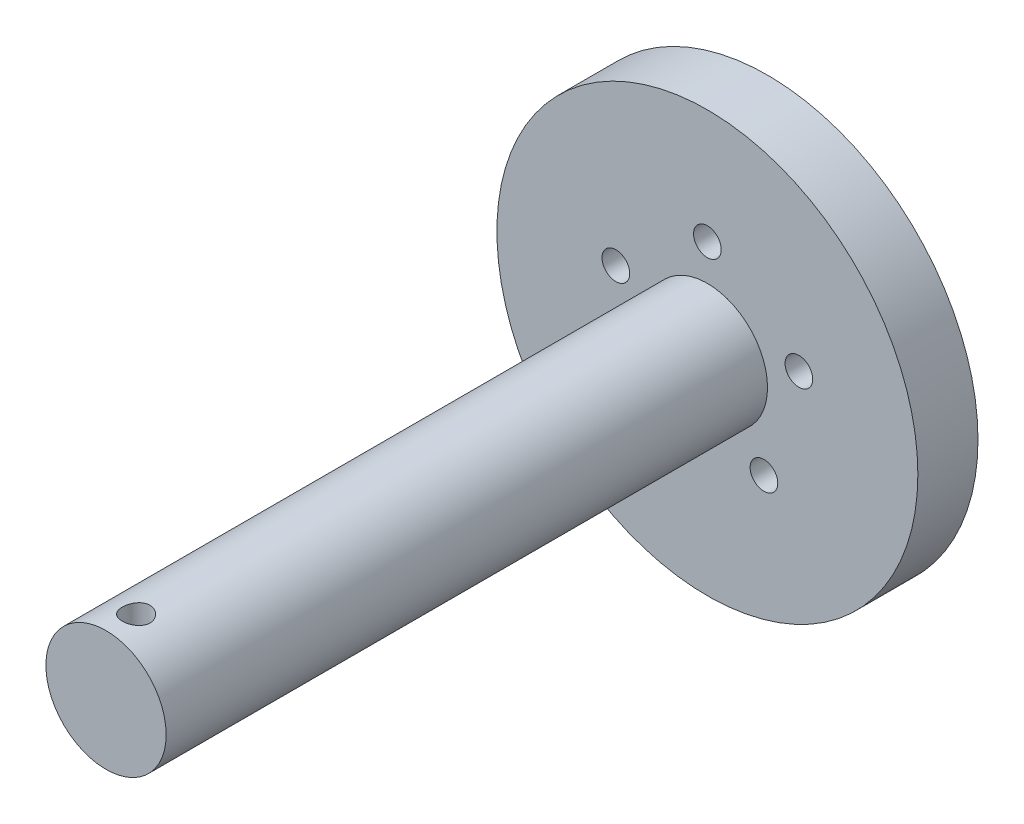
SolidWorks part; units mm, degrees
ref_plane "Front Plane" through (0, 0, 0) normal (0, 0, 1) x (1, 0, 0)
ref_plane "Top Plane" through (0, 0, 0) normal (0, 1, 0) x (1, 0, 0)
ref_plane "Right Plane" through (0, 0, 0) normal (1, 0, 0) x (0, 0, -1)
sketch "Sketch1" plane through (0, 0, 0) normal (0, 0, 1) x (1, 0, 0)
  line L0 (0, 0) -> (0, 20.32) construction
  line L1 (0, 0) -> (19.3255, 6.2792) construction
  line L2 (0, 0) -> (11.9438, -16.4392) construction
  line L3 (0, 0) -> (-11.9438, -16.4392) construction
  line L4 (0, 0) -> (-19.3255, 6.2792) construction
  circle A0 centre (0, 0) radius 44.45
  circle A1 centre (0, 20.32) radius 2.921
  circle A2 centre (19.3255, 6.2792) radius 2.921
  circle A3 centre (11.9438, -16.4392) radius 2.921
  circle A4 centre (-11.9438, -16.4392) radius 2.921
  circle A5 centre (-19.3255, 6.2792) radius 2.921
  point P15 (0, 0)
  dimension "D1" = 88.9
  dimension "D3" = 5.842
  dimension "D2" = 20.32
  dimension "D4" = 5
extrude "Boss-Extrude1" add sketch "Sketch1" along normal blind 12.7
sketch "Sketch2" plane through (0, 0, 12.7) normal (0, 0, 1) x (1, 0, 0)
  circle A0 centre (0, 0) radius 12.7
  dimension "D1" = 25.4
extrude "Boss-Extrude2" add sketch "Sketch2" along normal blind 127
sketch "Sketch3" plane through (0, 0, 139.7) normal (0, 0, 1) x (1, 0, 0)
  line L0 (0, 0) -> (0, -12.7) construction
  circle A0 centre (0, 0) radius 12.7 construction
ref_plane "Plane1" through (0, -12.7, 0) normal (0, -1, 0) x (-1, 0, 0)
sketch "Sketch4" plane through (0, -12.7, 0) normal (0, -1, 0) x (-1, 0, 0)
  line L0 (0, -139.7) -> (0, -133.35) construction
  line L1 (-12.7, -139.7) -> (12.7, -139.7) construction
  circle A0 centre (0, -133.35) radius 2.921
  dimension "D2" = 5.842
  dimension "D1" = 6.35
extrude "Cut-Extrude1" cut sketch "Sketch4" against normal up to next
